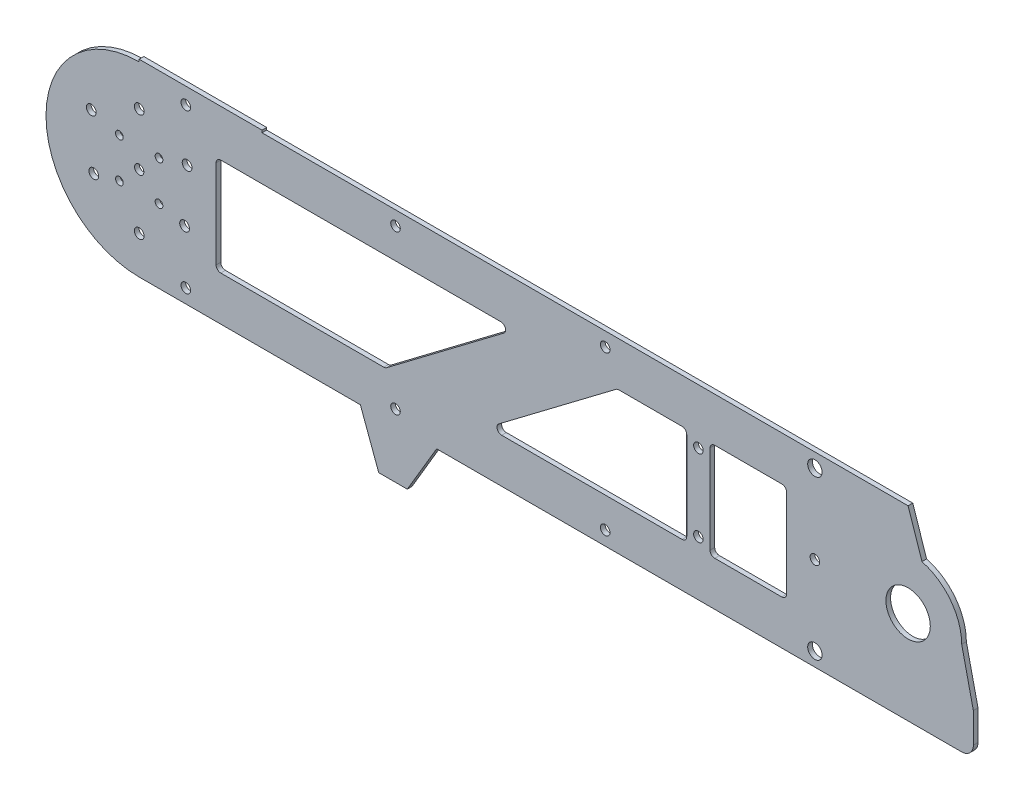
SolidWorks part; units mm, degrees
ref_plane "前视基准面" through (0, 0, 0) normal (0, 0, 1) x (1, 0, 0)
ref_plane "上视基准面" through (0, 0, 0) normal (0, 1, 0) x (1, 0, 0)
ref_plane "右视基准面" through (0, 0, 0) normal (1, 0, 0) x (0, 0, -1)
sketch "草图1" plane through (0, 0, 0) normal (0, 0, 1) x (1, 0, 0)
  line L0 (-1.4571, -0.1457) -> (37.8152, -22.8196) construction
  line L1 (-1.4571, -0.1457) -> (328.5429, -0.1457) construction
  line L8 (-1.4571, 39.8543) -> (328.5429, 39.8543)
  line L9 (-1.4571, -0.1457) -> (-1.4571, -8.6457) construction
  line L10 (-1.4571, -8.6457) -> (7.0429, -8.6457) construction
  line L11 (328.5429, -0.1457) -> (341.7814, 49.2612) construction
  line L12 (328.5429, -0.1457) -> (341.7814, -49.5526) construction
  line L20 (328.5429, 39.8543) -> (334.4957, 22.0706)
  line L23 (356.5429, -48.5797) -> (356.5429, -22.236) construction
  line L35 (113.6085, -61.4457) -> (126.1948, -40.1457)
  line L36 (113.6085, -61.4457) -> (101.3414, -61.4457)
  line L37 (101.3414, -61.4457) -> (93.4628, -40.1457)
  line L38 (93.4628, -40.1457) -> (-1.4571, -40.1457)
  line L39 (126.1948, -40.1457) -> (328.5429, -40.1457)
  line L48 (328.5429, -40.1457) -> (356.5429, -40.1457)
  line L49 (356.5429, -40.1457) -> (356.5429, -22.236)
  line L50 (351.5429, -0.1457) -> (356.5429, -22.236)
  circle A0 centre (-1.4571, -0.1457) radius 23.75 construction
  circle A1 centre (-1.4571, -0.1457) radius 22.5 construction
  circle A2 centre (-1.4571, -23.8957) radius 2.1
  circle A3 centre (18.0284, -11.3957) radius 2.1
  circle A4 centre (-1.4571, -0.1457) radius 40 construction
  circle A6 centre (-1.4571, -0.1457) radius 2
  circle A12 centre (328.5429, -0.1457) radius 40 construction
  arc A16 (-1.4571, -40.1457) -> (-1.4571, 39.8543) centre (-1.4571, -0.1457) cw
  circle A22 centre (328.5429, -0.1457) radius 9.52
  circle A23 centre (288.5429, -0.1457) radius 2.05
  circle A24 centre (238.5429, 16.3543) radius 2.05
  circle A25 centre (238.5429, -16.6457) radius 2.05
  circle A26 centre (-20.9427, -11.3957) radius 2.1
  circle A27 centre (-22.0252, 11.7293) radius 2.1
  circle A28 centre (-1.4571, 22.3543) radius 2.1
  circle A29 centre (19.111, 11.7293) radius 2.1
  circle A36 centre (328.5429, -0.1457) radius 23 construction
  circle A37 centre (7.0429, -8.6457) radius 1.65
  circle A38 centre (-9.9571, -8.6457) radius 1.65
  circle A39 centre (-9.9571, 8.3543) radius 1.65
  circle A40 centre (7.0429, 8.3543) radius 1.65
  arc A45 (334.4957, 22.0706) -> (351.5429, -0.1457) centre (328.5429, -0.1457) cw
  dimension "D1" = 45
  dimension "D2" = 3
  dimension "D3" = 4.2
  dimension "D4" = 19.04
  dimension "D5" = 80
  dimension "D6" = 80
  dimension "D7" = 4
  dimension "D11" = 4.1
  dimension "D12" = 47.5
  dimension "D13" = 4
  dimension "D14" = 105
  dimension "D8" = 330
  dimension "D9" = 50
  dimension "D10" = 16.5
  dimension "D15" = 28
extrude "凸台-拉伸1" add sketch "草图1" along normal blind 2
sketch "草图3" plane through (0, 0, 2) normal (0, 0, 1) x (1, 0, 0)
  line L0 (-1.4571, 39.8543) -> (-1.4571, 40.8343)
  line L5 (-1.4571, 40.8343) -> (51.269, 40.8343)
  line L6 (51.269, 40.8343) -> (51.269, 39.8543)
  line L8 (328.5429, 39.8543) -> (-1.4571, 39.8543) construction
  line L9 (51.269, 39.8543) -> (-1.4571, 39.8543)
  dimension "D4" = 0.98
extrude "凸台-拉伸2" add sketch "草图3" against normal blind 2
sketch "草图2" plane through (0, 0, 2) normal (0, 0, 1) x (1, 0, 0)
  line L0 (18.5429, 33.8543) -> (198.5429, 33.8543) construction
  line L1 (108.5429, -34.1457) -> (198.5429, 33.8543) construction
  line L2 (18.5429, 33.8543) -> (18.5429, -34.1457) construction
  line L3 (18.5429, -34.1457) -> (108.5429, -34.1457) construction
  line L4 (31.5429, -21.1457) -> (104.1839, -21.1457)
  line L5 (104.1839, -21.1457) -> (159.7721, 20.8543)
  line L6 (31.5429, 20.8543) -> (159.7721, 20.8543)
  line L7 (31.5429, 20.8543) -> (31.5429, -21.1457)
  line L8 (108.5429, -34.1457) -> (288.5429, -34.1457) construction
  line L9 (288.5429, -34.1457) -> (288.5429, 33.8543) construction
  line L10 (288.5429, 33.8543) -> (198.5429, 33.8543) construction
  line L11 (276.3527, 20.8543) -> (203.7117, 20.8543) construction
  line L12 (148.1234, -21.1457) -> (203.7117, 20.8543)
  line L13 (148.1234, -21.1457) -> (276.3527, -21.1457) construction
  line L14 (276.3527, -21.1457) -> (276.3527, 20.8543)
  line L15 (233.5429, 20.8543) -> (233.5429, -21.1457)
  line L16 (243.5429, 20.8543) -> (243.5429, -21.1457)
  line L17 (238.5429, 16.3543) -> (238.5429, -16.6457) construction
  line L18 (233.5429, 20.8543) -> (203.7117, 20.8543)
  line L19 (243.5429, 20.8543) -> (276.3527, 20.8543)
  line L20 (243.5429, -21.1457) -> (276.3527, -21.1457)
  line L21 (233.5429, -21.1457) -> (148.1234, -21.1457)
  line L22 (-1.4571, -40.1457) -> (342.5707, -40.1457) construction
  circle A0 centre (18.5429, 33.8543) radius 2.05
  circle A1 centre (108.5429, 33.8543) radius 2.05
  circle A2 centre (198.5429, 33.8543) radius 2.05
  circle A3 centre (288.5429, 33.8543) radius 2.05 construction
  circle A4 centre (108.5429, -34.1457) radius 2.05
  circle A5 centre (198.5429, -34.1457) radius 2.05
  circle A6 centre (288.5429, -34.1457) radius 2.05 construction
  circle A8 centre (288.5429, -34.1457) radius 3.1
  circle A10 centre (18.5429, -34.1457) radius 2.05
  circle A11 centre (288.5429, 33.8543) radius 3.1
  point P2 (-1.4571, -0.1457)
  dimension "D1" = 4.1
  dimension "D14" = 68
  dimension "D2" = 34
  dimension "D3" = 20
  dimension "D4" = 10
  dimension "D13" = 6
extrude "切除-拉伸1" cut sketch "草图2" against normal blind 4
fillet "圆角1" radius 2 12 edges at (243.5429, -21.1457, 1) (243.5429, 20.8543, 1) (276.3527, -21.1457, 1) (276.3527, 20.8543, 1) (233.5429, -21.1457, 1) (233.5429, 20.8543, 1) (203.7117, 20.8543, 1) (148.1234, -21.1457, 1) (159.7721, 20.8543, 1) (104.1839, -21.1457, 1) (31.5429, -21.1457, 1) (31.5429, 20.8543, 1)
fillet "圆角2" radius 5 1 edges at (356.5429, -40.1457, 1)
